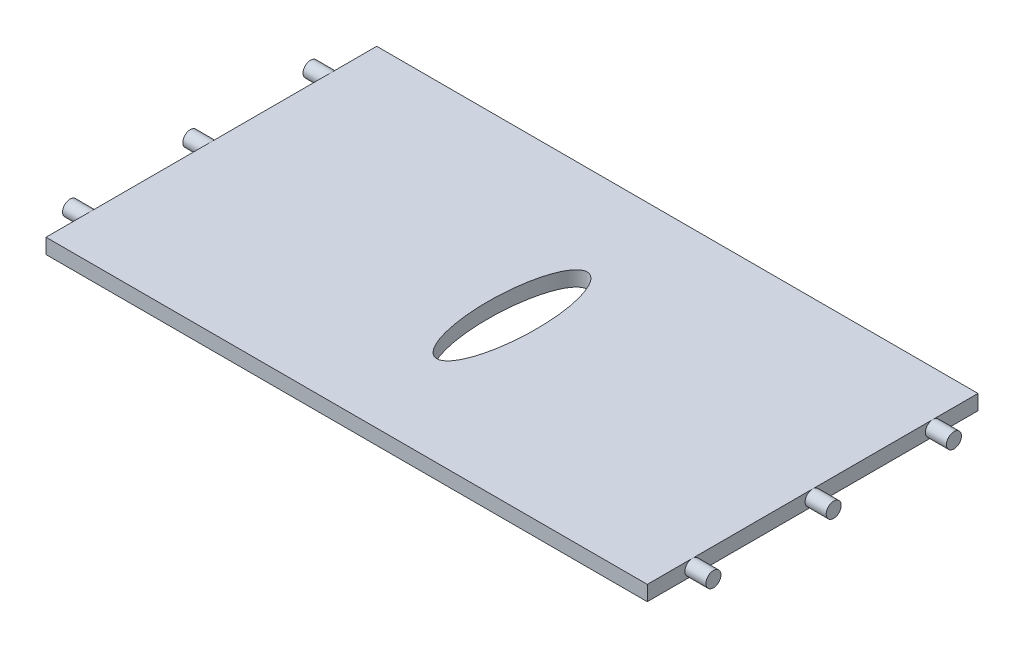
SolidWorks part; units mm, degrees
ref_plane "Front Plane" through (0, 0, 0) normal (0, 0, 1) x (1, 0, 0)
ref_plane "Top Plane" through (0, 0, 0) normal (0, 1, 0) x (1, 0, 0)
ref_plane "Right Plane" through (0, 0, 0) normal (1, 0, 0) x (0, 0, -1)
sketch "Sketch1" plane through (0, 0, 0) normal (0, 1, 0) x (1, 0, 0)
  line L1 (-100, -55) -> (100, -55)
  line L2 (-100, -55) -> (-100, 55)
  line L3 (-100, 55) -> (100, 55)
  line L4 (100, -55) -> (100, 55)
  line L5 (-100, -55) -> (100, 55) construction
  line L6 (-100, 55) -> (100, -55) construction
  point P0 (0, 0)
  dimension "D1" = 200
  dimension "D2" = 110
extrude "Boss-Extrude1" add sketch "Sketch1" along normal blind 5
sketch "Sketch2" plane through (-100, 0, 0) normal (-1, 0, 0) x (0, 0, 1)
  line L0 (-55, 0) -> (55, 0) construction
  circle A0 centre (-40, 2.5) radius 2.5
  circle A1 centre (0, 2.5) radius 2.5
  circle A2 centre (40, 2.5) radius 2.5
  dimension "D1" = 5
  dimension "D3" = 5
  dimension "D6" = 5
  dimension "D2" = 2.5
  dimension "D4" = 2.5
  dimension "D5" = 2.5
  dimension "D7" = 40
  dimension "D8" = 40
extrude "Boss-Extrude2" add sketch "Sketch2" along normal blind 7 and the other way blind 207
sketch "Sketch3" plane through (0, 5, 0) normal (0, 1, 0) x (1, 0, 0)
  ellipse E0 centre (0, 0) end of major axis (0, 25) minor radius 8
  point P1 (0, 0)
  point P7 (0, 0)
  point P9 (8.302, -1.9602)
  dimension "D1" = 25
  dimension "D2" = 8
extrude "Cut-Extrude1" cut sketch "Sketch3" against normal blind 10
